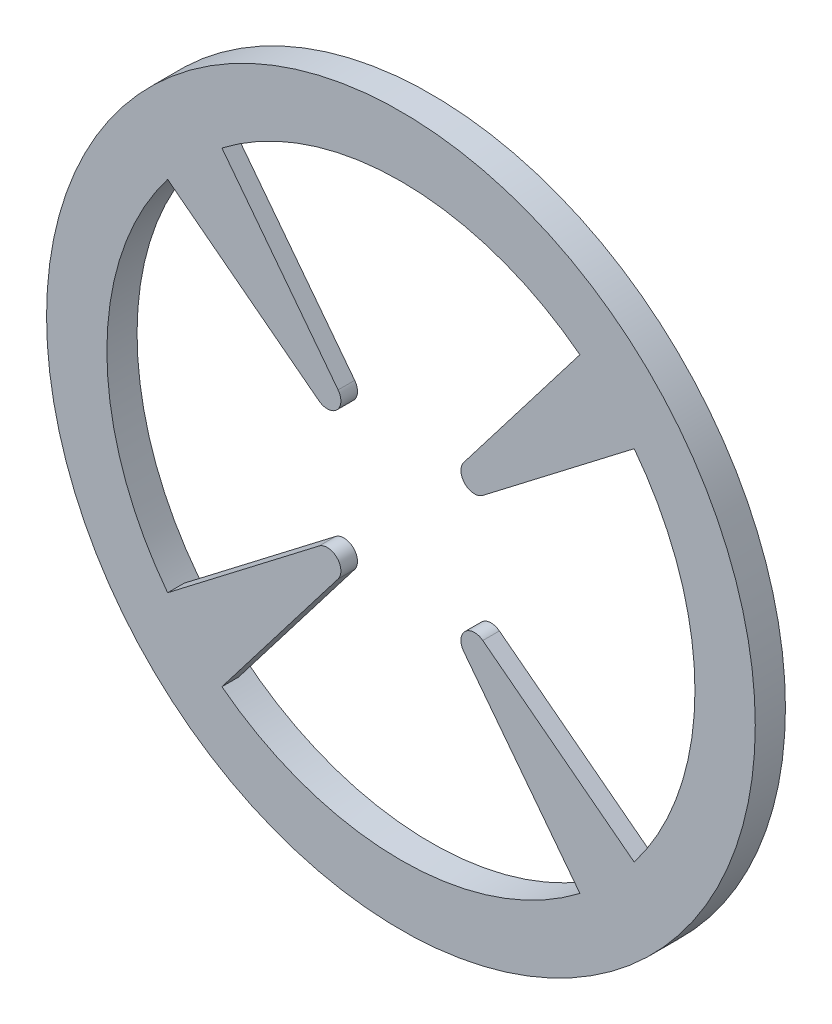
SolidWorks part; units mm, degrees
ref_plane "前基準面" through (0, 0, 0) normal (0, 0, 1) x (1, 0, 0)
ref_plane "上基準面" through (0, 0, 0) normal (0, 1, 0) x (1, 0, 0)
ref_plane "右基準面" through (0, 0, 0) normal (1, 0, 0) x (0, 0, -1)
sketch "草圖1" plane through (0, 0, 0) normal (0, 0, 1) x (1, 0, 0)
  circle A0 centre (0, 0) radius 1.1748
  circle A1 centre (0, 0) radius 0.9748
  dimension "D1" = 0.2
extrude "填料-伸長1" add sketch "草圖1" along normal blind 0.1
sketch "草圖2" plane through (0, 0, 0.1) normal (0, 0, 1) x (1, 0, 0)
  line L0 (0, 0) -> (0, 1.565) construction
  line L1 (0, 0) -> (-1.8584, 0) construction
  line L2 (-0.0447, 0.3392) -> (-0.1272, 0.9664)
  line L3 (0.0447, 0.3392) -> (0.1272, 0.9664)
  line L4 (0.2714, 0.2082) -> (0.7733, 0.5934)
  line L5 (0.2082, 0.2714) -> (0.5934, 0.7733)
  line L6 (0.2082, -0.2714) -> (0.5934, -0.7733)
  line L7 (0.2714, -0.2082) -> (0.7733, -0.5934)
  line L8 (-0.2714, -0.2082) -> (-0.7733, -0.5934)
  line L9 (-0.2082, -0.2714) -> (-0.5934, -0.7733)
  line L10 (-0.2082, 0.2714) -> (-0.5934, 0.7733)
  line L11 (-0.2714, 0.2082) -> (-0.7733, 0.5934)
  circle A0 centre (0, 0) radius 0.3
  circle A1 centre (0, 0) radius 0.9748 construction
  arc A3 (-0.0447, 0.3392) -> (0.0447, 0.3392) centre (0, 0.345) ccw
  arc A4 (0.1272, 0.9664) -> (-0.1272, 0.9664) centre (0, 0) ccw
  arc A5 (-0.9748, 0) -> (0.9748, 0) centre (0, 0) ccw
  arc A6 (0.7733, 0.5934) -> (0.5934, 0.7733) centre (0, 0) ccw
  arc A7 (0.2082, 0.2714) -> (0.2714, 0.2082) centre (0.244, 0.244) ccw
  arc A8 (0.5934, -0.7733) -> (0.7733, -0.5934) centre (0, 0) ccw
  arc A9 (0.2714, -0.2082) -> (0.2082, -0.2714) centre (0.244, -0.244) ccw
  arc A10 (-0.7733, -0.5934) -> (-0.5934, -0.7733) centre (0, 0) ccw
  arc A11 (-0.2082, -0.2714) -> (-0.2714, -0.2082) centre (-0.244, -0.244) ccw
  arc A12 (-0.5934, 0.7733) -> (-0.7733, 0.5934) centre (0, 0) ccw
  arc A13 (-0.2714, 0.2082) -> (-0.2082, 0.2714) centre (-0.244, 0.244) ccw
  point P23 (0, 0)
  point P34 (0, 0)
  point P41 (0, 0)
  circle M4 centre (0, 0) radius 0.9748
  dimension "D1" = 7.5
  dimension "D3" = 2
  dimension "D4" = 4
  dimension "D2" = 7.5
extrude "填料-伸長2" add sketch "草圖2" against normal blind 0.055 contours L11 A13 L10 M4 | L5 A7 L4 M4 | L7 A9 L6 M4 | A11 L8 L9 M4
